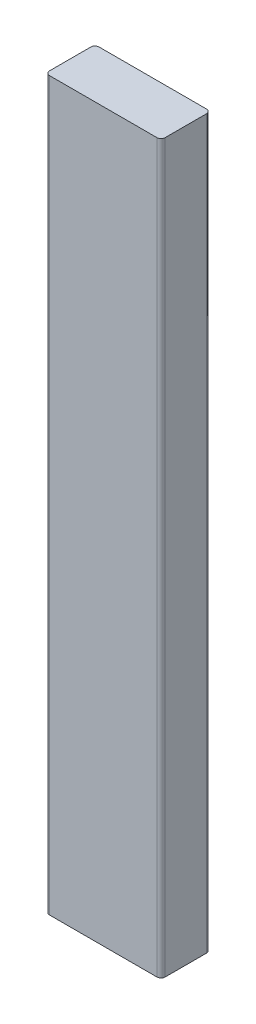
SolidWorks part; units mm, degrees
ref_plane "Front" through (0, 0, 0) normal (0, 0, 1) x (1, 0, 0)
ref_plane "Top" through (0, 0, 0) normal (0, 1, 0) x (1, 0, 0)
ref_plane "Right" through (0, 0, 0) normal (1, 0, 0) x (0, 0, -1)
sketch "Sketch1" plane through (0, 0, 0) normal (0, 1, 0) x (1, 0, 0)
  line L1 (41.275, -19.05) -> (-41.275, -19.05)
  line L2 (44.45, -15.875) -> (44.45, 15.875)
  line L3 (41.275, 19.05) -> (-41.275, 19.05)
  line L4 (-44.45, -15.875) -> (-44.45, 15.875)
  line L5 (44.45, -19.05) -> (-44.45, 19.05) construction
  line L6 (44.45, 19.05) -> (-44.45, -19.05) construction
  arc A0 (-41.275, -19.05) -> (-44.45, -15.875) centre (-41.275, -15.875) cw
  arc A1 (41.275, -19.05) -> (44.45, -15.875) centre (41.275, -15.875) ccw
  arc A2 (44.45, 15.875) -> (41.275, 19.05) centre (41.275, 15.875) ccw
  arc A3 (-41.275, 19.05) -> (-44.45, 15.875) centre (-41.275, 15.875) ccw
  point P0 (0, 0)
  dimension "D1" = 3.175
  dimension "D2" = 38.1
  dimension "D3" = 88.9
extrude "Boss-Extrude1" add sketch "Sketch1" along normal blind 558.8
equation "\"L\" = 22"
equation "\"D1@Boss-Extrude1\"=\"L\""
